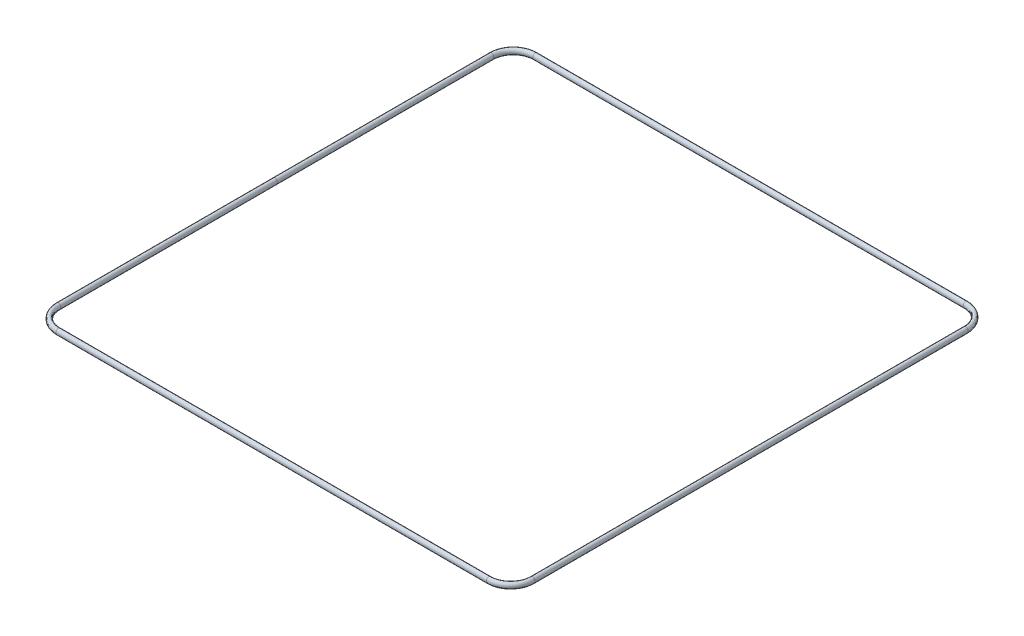
SolidWorks part; units mm, degrees
material "Rubber"
ref_plane "Front Plane" through (0, 0, 0) normal (0, 0, 1) x (1, 0, 0)
ref_plane "Top Plane" through (0, 0, 0) normal (0, 1, 0) x (1, 0, 0)
ref_plane "Right Plane" through (0, 0, 0) normal (1, 0, 0) x (0, 0, -1)
sketch "Sketch1" plane through (0, 0, 0) normal (0, 1, 0) x (1, 0, 0)
  line L1 (-127.381, -141.097) -> (127.381, -141.097)
  line L2 (-140.335, -128.143) -> (-140.335, 128.143)
  line L3 (-127.381, 141.097) -> (127.381, 141.097)
  line L4 (140.335, -128.143) -> (140.335, 128.143)
  line L5 (-140.335, -141.097) -> (140.335, 141.097) construction
  line L6 (-140.335, 141.097) -> (140.335, -141.097) construction
  arc A0 (127.381, 141.097) -> (140.335, 128.143) centre (127.381, 128.143) cw
  arc A1 (127.381, -141.097) -> (140.335, -128.143) centre (127.381, -128.143) ccw
  arc A2 (-127.381, -141.097) -> (-140.335, -128.143) centre (-127.381, -128.143) cw
  arc A3 (-140.335, 128.143) -> (-127.381, 141.097) centre (-127.381, 128.143) cw
  point P0 (0, 0)
  dimension "D3" = 12.954
  dimension "D1" = 280.67
  dimension "D2" = 282.194
sketch "Sketch44" plane through (0, 0, 0) normal (0, 0, 1) x (1, 0, 0)
  line L0 (-140.335, 0) -> (140.335, 0) construction
  line L1 (-127.381, 0) -> (-140.335, 0) construction
  ellipse E0 centre (-140.335, 0) end of major axis (-140.335, 1.78) minor radius 1.397
  dimension "D1" = 3.56
  dimension "D2" = 2.794
sweep "Sweep2" add profiles "Sketch44" path "Sketch1"
ref_plane "Plane1" through (0, 1.778, 0) normal (0, 1, 0) x (1, 0, 0)
ref_plane "Plane2" through (0, -1.778, 0) normal (0, 1, 0) x (1, 0, 0)
